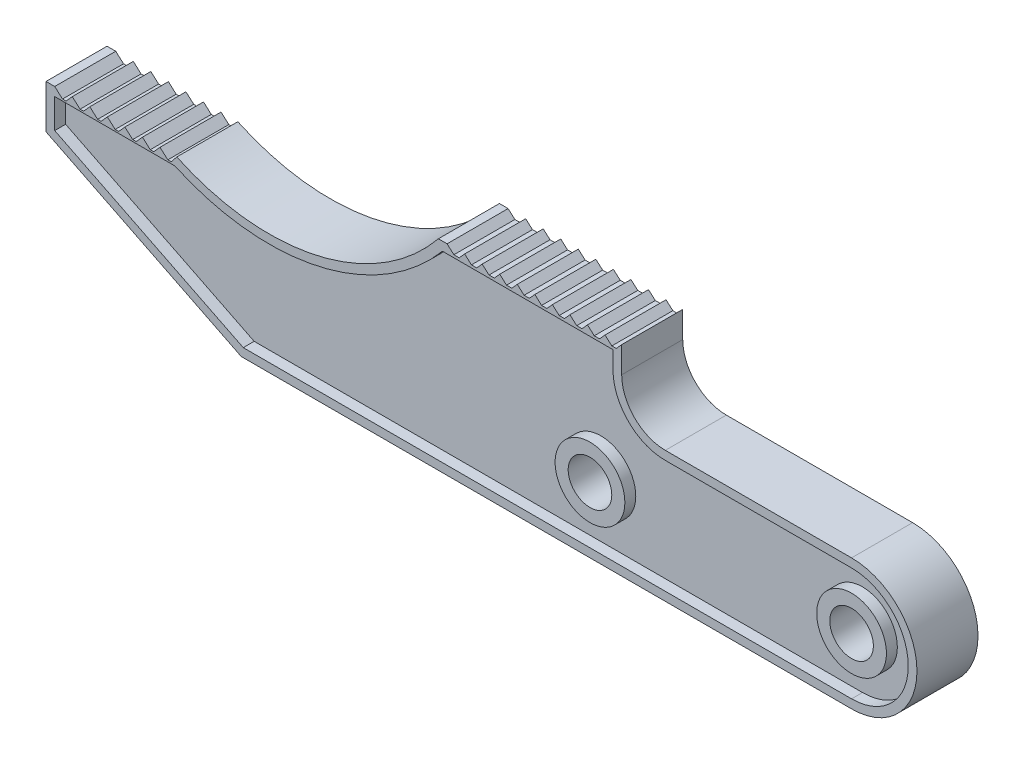
SolidWorks part; units mm, degrees
ref_plane "Front Plane" through (0, 0, 0) normal (0, 0, 1) x (1, 0, 0)
ref_plane "Top Plane" through (0, 0, 0) normal (0, 1, 0) x (1, 0, 0)
ref_plane "Right Plane" through (0, 0, 0) normal (1, 0, 0) x (0, 0, -1)
sketch "Sketch1" plane through (0, 0, 0) normal (0, 0, 1) x (1, 0, 0)
  line L0 (39.967, 0) -> (-30.033, 0)
  line L1 (-30.033, 0) -> (-52.4209, 11.1257)
  line L2 (-52.4209, 11.1257) -> (-52.4209, 16.1257)
  line L3 (-52.4209, 16.1257) -> (-37.4209, 16.1257)
  line L4 (-7.4209, 23) -> (13.6035, 23)
  line L5 (39.967, 15) -> (18.6035, 15)
  line L6 (13.6035, 23) -> (13.6035, 20)
  arc A0 (-37.4209, 16.1257) -> (-7.4209, 23) centre (-26.8215, 38.7676) ccw
  arc A2 (39.967, 0) -> (39.967, 15) centre (39.967, 7.5) ccw
  arc A3 (13.6035, 20) -> (18.6035, 15) centre (18.6035, 20) ccw
  circle A4 centre (39.967, 7.5) radius 2.5
  circle A5 centre (9.967, 7.5) radius 2.5
  dimension "D7" = 25
  dimension "D8" = 15
  dimension "D9" = 5
  dimension "D5" = 5
  dimension "D1" = 70
  dimension "D2" = 25
  dimension "D3" = 5
  dimension "D4" = 15
  dimension "D6" = 30
  dimension "D10" = 3
  dimension "D11" = 30
extrude "Boss-Extrude1" add sketch "Sketch1" along normal mid plane 7
sketch "Sketch2" plane through (0, 0, 3.5) normal (0, 0, 1) x (1, 0, 0)
  line L14 (39.967, 14) -> (18.6035, 14)
  line L15 (12.6035, 20) -> (12.6035, 22)
  line L16 (12.6035, 22) -> (-6.9507, 22)
  line L17 (-37.6411, 15.1257) -> (-51.4209, 15.1257)
  line L18 (-51.4209, 15.1257) -> (-51.4209, 11.7454)
  line L19 (-51.4209, 11.7454) -> (-29.7982, 1)
  line L20 (-29.7982, 1) -> (39.967, 1)
  line L21 (39.967, 14) -> (18.6035, 14)
  line L22 (12.6035, 20) -> (12.6035, 22)
  line L23 (12.6035, 22) -> (-6.9507, 22)
  line L24 (-37.6411, 15.1257) -> (-51.4209, 15.1257)
  line L25 (-51.4209, 15.1257) -> (-51.4209, 11.7454)
  line L26 (-51.4209, 11.7454) -> (-29.7982, 1)
  line L27 (-29.7982, 1) -> (39.967, 1)
  arc A6 (39.967, 1) -> (39.967, 14) centre (39.967, 7.5) ccw
  arc A7 (12.6035, 20) -> (18.6035, 14) centre (18.6035, 20) ccw
  arc A8 (-37.6411, 15.1257) -> (-6.9507, 22) centre (-26.8215, 38.7676) ccw
  arc A9 (39.967, 1) -> (39.967, 14) centre (39.967, 7.5) ccw
  arc A10 (12.6035, 20) -> (18.6035, 14) centre (18.6035, 20) ccw
  arc A11 (-37.6411, 15.1257) -> (-6.9507, 22) centre (-26.8215, 38.7676) ccw
  dimension "D1" = 1
extrude "Cut-Extrude1" cut sketch "Sketch2" against normal blind 1.25
sketch "Sketch3" plane through (0, 0, 2.25) normal (0, 0, 1) x (1, 0, 0)
  circle A11 centre (9.967, 7.5) radius 4
  circle A12 centre (9.967, 7.5) radius 4
  circle A13 centre (9.967, 7.5) radius 2.5
  circle A14 centre (39.967, 7.5) radius 4
  circle A15 centre (39.967, 7.5) radius 4
  circle A16 centre (39.967, 7.5) radius 2.5
  dimension "D1" = 1.5
  dimension "D2" = 1.5
extrude "Boss-Extrude4" add sketch "Sketch3" along normal blind 1.25
mirror "Mirror1" about plane through (0, 0, 0) normal (0, 0, 1) of "Boss-Extrude4", "Cut-Extrude1"
sketch "Sketch4" plane through (0, 0, 3.5) normal (0, 0, 1) x (1, 0, 0)
  line L0 (-52.4209, 16.1257) -> (-51.4209, 16.1257)
  line L1 (-37.4209, 16.1257) -> (-52.4209, 16.1257) construction
  line L2 (-51.4209, 16.1257) -> (-50.5265, 15.3257)
  line L3 (-37.6411, 15.1257) -> (-51.4209, 15.1257) construction
  line L4 (-50.124, 15.3257) -> (-49.4085, 16.1257)
  line L5 (-49.4085, 16.1257) -> (-48.514, 15.3257)
  line L6 (-48.1115, 15.3257) -> (-47.396, 16.1257)
  line L7 (-47.396, 16.1257) -> (-46.5016, 15.3257)
  line L8 (-46.0991, 15.3257) -> (-45.3835, 16.1257)
  line L9 (-45.3835, 16.1257) -> (-44.4891, 15.3257)
  line L11 (-44.0866, 15.3257) -> (-43.3711, 16.1257)
  line L12 (-43.3711, 16.1257) -> (-42.4766, 15.3257)
  line L13 (-42.0742, 15.3257) -> (-41.3586, 16.1257)
  line L14 (-41.3586, 16.1257) -> (-40.4642, 15.3257)
  line L15 (-40.0617, 15.3257) -> (-39.3462, 16.1257)
  line L16 (-39.3462, 16.1257) -> (-38.4517, 15.3257)
  line L17 (-38.0667, 15.3257) -> (-37.4209, 16.1257)
  line L18 (-50.5265, 15.3257) -> (-38.0667, 15.3257)
  line L19 (-51.4209, 16.1257) -> (-37.4209, 16.1257)
  line M21 (-37.4209, 16.1257) -> (-52.4209, 16.1257)
  dimension "D1" = 1
  dimension "D3" = 0.2
extrude "Cut-Extrude2" cut sketch "Sketch4" against normal through all contours L9 L18 L11 M21 | L12 L18 L13 M21 | L14 L18 L15 M21 | L16 L18 L17 M21 | L7 L18 L8 M21 | L5 L18 L6 M21 | L2 L18 L4 M21
sketch "Sketch5" plane through (0, 0, 3.5) normal (0, 0, 1) x (1, 0, 0)
  line L0 (-7.4209, 23) -> (-6.4209, 23)
  line L1 (13.6035, 23) -> (-7.4209, 23) construction
  line L2 (-6.4209, 23) -> (-5.6425, 22.3038)
  line L3 (-6.4209, 23) -> (13.6035, 23)
  line L4 (-5.0312, 22.3038) -> (-4.4085, 23)
  line L5 (-4.4085, 23) -> (-3.6301, 22.3038)
  line L6 (-3.0187, 22.3038) -> (-2.396, 23)
  line L7 (-2.396, 23) -> (-1.6176, 22.3038)
  line L8 (12.9843, 22.3038) -> (13.6035, 23)
  line L9 (-1.0062, 22.3038) -> (-0.3835, 23)
  line L10 (-0.3835, 23) -> (0.3948, 22.3038)
  line L11 (1.0062, 22.3038) -> (1.6289, 23)
  line L12 (1.6289, 23) -> (2.4073, 22.3038)
  line L13 (3.0187, 22.3038) -> (3.6414, 23)
  line L14 (3.6414, 23) -> (4.4198, 22.3038)
  line L15 (5.0311, 22.3038) -> (5.6538, 23)
  line L16 (5.6538, 23) -> (6.4322, 22.3038)
  line L17 (7.0436, 22.3038) -> (7.6663, 23)
  line L18 (7.6663, 23) -> (8.4447, 22.3038)
  line L19 (9.0561, 22.3038) -> (9.6788, 23)
  line L20 (9.6788, 23) -> (10.4572, 22.3038)
  line L21 (11.0685, 22.3038) -> (11.6912, 23)
  line L22 (11.6912, 23) -> (12.4696, 22.3038)
  line L24 (-5.6425, 22.3038) -> (12.9843, 22.3038)
  line M16 (13.6035, 23) -> (-7.4209, 23)
  dimension "D1" = 1
extrude "Cut-Extrude3" cut sketch "Sketch5" against normal through all contours L2 L24 L4 L3 | L5 L24 L6 L3 | L7 L24 L9 L3 | L10 L24 L11 L3 | L12 L24 L13 L3 | L14 L24 L15 L3 | L16 L24 L17 L3 | L18 L24 L19 L3 | L20 L24 L21 L3 | L22 L24 L8 M16
